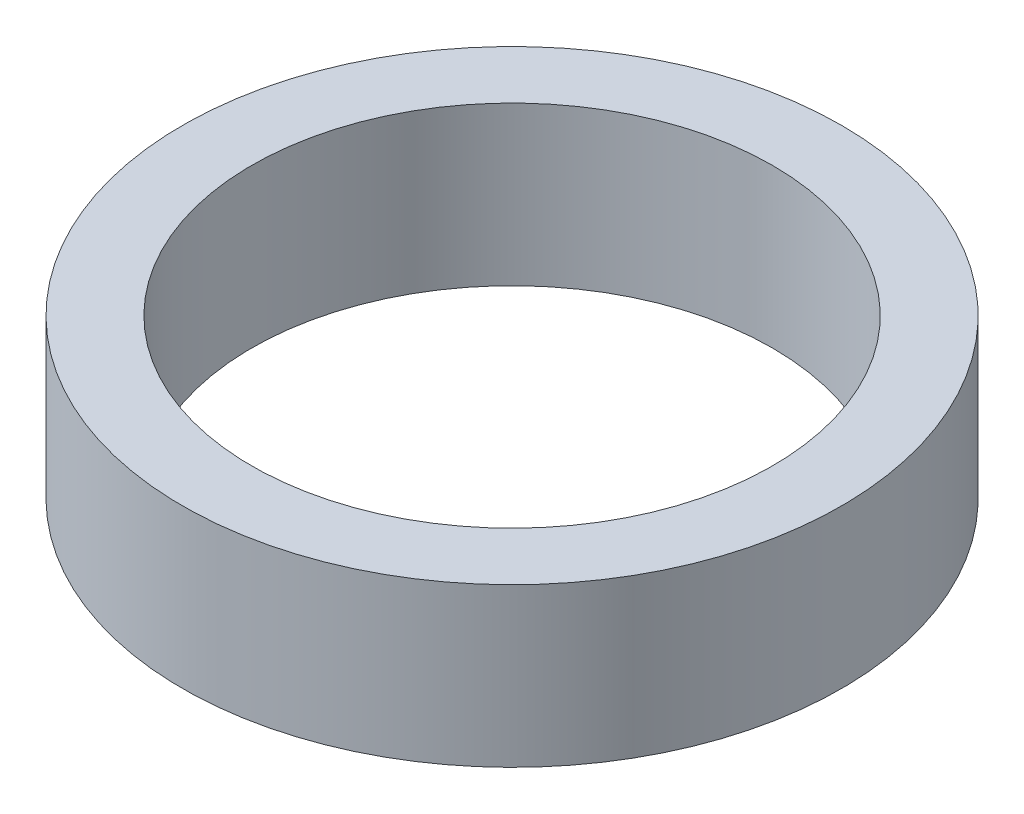
SolidWorks part; units mm, degrees
material "ABS"
ref_plane "Front Plane" through (0, 0, 0) normal (0, 0, 1) x (1, 0, 0)
ref_plane "Top Plane" through (0, 0, 0) normal (0, 1, 0) x (1, 0, 0)
ref_plane "Right Plane" through (0, 0, 0) normal (1, 0, 0) x (0, 0, -1)
sketch "Sketch1" plane through (0, 0, 0) normal (0, 1, 0) x (1, 0, 0)
  circle A0 centre (0, 0) radius 2.5082
  circle A1 centre (0, 0) radius 3.175
  dimension "D1" = 6.35
  dimension "D2" = 5.0165
extrude "Boss-Extrude1" add sketch "Sketch1" along normal blind 1.524
